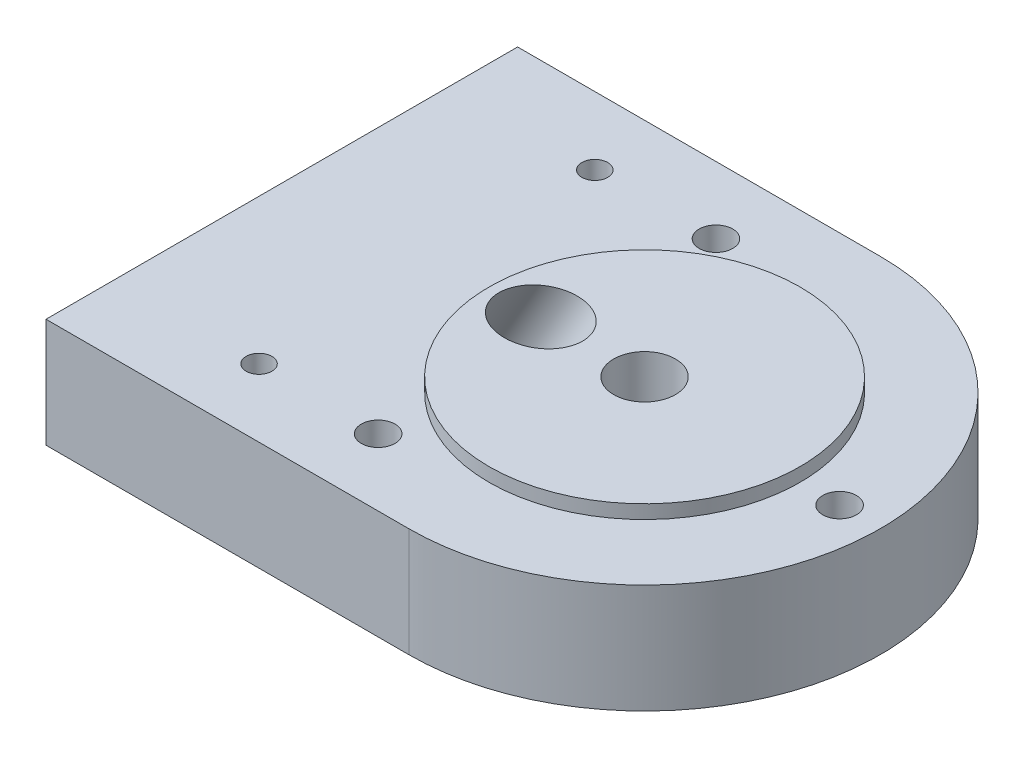
SolidWorks part; units mm, degrees
material "6061-T6 (SS)"
ref_plane "Front Plane" through (0, 0, 0) normal (0, 0, 1) x (1, 0, 0)
ref_plane "Top Plane" through (0, 0, 0) normal (0, 1, 0) x (1, 0, 0)
ref_plane "Right Plane" through (0, 0, 0) normal (1, 0, 0) x (0, 0, -1)
sketch "Sketch1" plane through (0, 0, 0) normal (0, 1, 0) x (1, 0, 0)
  line L1 (0, 0) -> (31.75, 0)
  line L2 (0, 0) -> (0, 41.275)
  line L3 (0, 41.275) -> (31.75, 41.275)
  line L4 (31.75, 0) -> (31.75, 41.275) construction
  arc A0 (31.75, 41.275) -> (31.75, 0) centre (31.75, 20.6375) cw
  dimension "D1" = 41.275
  dimension "D2" = 31.75
extrude "Boss-Extrude1" add sketch "Sketch1" along normal blind 9.5504
sketch "Sketch2" plane through (0, 9.5504, 0) normal (0, 1, 0) x (1, 0, 0)
  line L0 (31.75, 41.275) -> (31.75, 0) construction
  circle A0 centre (31.75, 20.6375) radius 13.6144
  arc A1 (31.75, 0) -> (31.75, 41.275) centre (31.75, 20.6375) ccw construction
  dimension "D1" = 27.2288
extrude "Boss-Extrude2" add sketch "Sketch2" along normal blind 1.1938
sketch "Sketch3" plane through (0, 10.7442, 0) normal (0, 1, 0) x (1, 0, 0)
  line L0 (18.1356, 20.6375) -> (45.3644, 20.6375) construction
  line L1 (31.75, 34.2519) -> (31.75, 7.0231) construction
  circle A0 centre (31.75, 20.6375) radius 13.6144 construction
  circle A1 centre (31.75, 20.6375) radius 13.6144 construction
  circle A3 centre (23.2156, 35.4203) radius 1.4732
  circle A4 centre (48.8188, 20.6375) radius 1.4732
  circle A5 centre (23.2156, 5.8547) radius 1.4732
  dimension "D4" = 2.9464
  dimension "D5" = 2.9464
  dimension "D6" = 2.9464
  dimension "D1" = 8.5344
  dimension "D2" = 14.7828
  dimension "D3" = 14.7828
  dimension "D7" = 17.0688
extrude "Cut-Extrude1" cut sketch "Sketch3" against normal through all
sketch "Sketch6" plane through (0, 0, 0) normal (0, -1, 0) x (-1, 0, 0)
  line L0 (-12.7, 0) -> (-12.7, 41.275) construction
  line L1 (0, 0) -> (-31.75, 0) construction
  line L2 (-31.75, 41.275) -> (0, 41.275) construction
  line L3 (0, 20.6375) -> (-52.3875, 20.6375) construction
  line L4 (0, 41.275) -> (0, 0) construction
  line L5 (-31.75, 0) -> (-31.75, 41.275) construction
  line L6 (-12.7, 5.9436) -> (0, 5.9436) construction
  line L7 (-12.7, 35.3314) -> (0, 35.3314) construction
  arc A0 (-31.75, 41.275) -> (-31.75, 0) centre (-31.75, 20.6375) ccw construction
  dimension "D1" = 12.7
  dimension "D2" = 29.3878
hole_wizard "#4-40 Tapped Hole1" positions "Sketch7" profile "Sketch8" tap size "#4-40" standard "ANSI Inch" end condition through all
sketch "Sketch7" plane through (0, 0, 0) normal (0, -1, 0) x (-1, 0, 0)
  point P0 (-12.7, 5.9436)
  point P3 (-12.7, 35.3314)
cosmetic thread "Hole Thread2" parameters "D2"=2.8448
cosmetic thread "Hole Thread3" parameters "D2"=2.8448
sketch "Sketch8" plane through (12.7, 0, -5.9436) normal (1, 0, 0) x (0, 0, -1)
  line L0 (0, 0) -> (0, 10.7442)
  line L1 (0, 10.7442) -> (1.1303, 10.7442)
  line L2 (1.1303, 10.7442) -> (1.1303, 0)
  line L5 (1.1303, 0) -> (0, 0)
  line L11 (0, -6.35) -> (0, 107.95) construction
  dimension "Thru Tap Drill Dia." = 2.2606
  dimension "Thru Tap Drill Depth" = 10.7442
hole_wizard "1/4-28 Tapped Hole1" positions "Sketch9" profile "Sketch10" tap size "1/4-28" standard "ANSI Inch" end condition through all
sketch "Sketch9" plane through (0, 0, 0) normal (0, -1, 0) x (-1, 0, 0)
  line L0 (-31.75, 0) -> (-31.75, 41.275) construction
  point P0 (-31.75, 20.6375)
sketch "Sketch10" plane through (31.75, 0, -20.6375) normal (1, 0, 0) x (0, 0, -1)
  line L0 (0, 0) -> (0, 10.7442)
  line L1 (0, 10.7442) -> (2.7051, 10.7442)
  line L2 (2.7051, 10.7442) -> (2.7051, 1.1249)
  line L3 (2.7051, 1.1249) -> (3.683, 0)
  line L5 (3.683, 0) -> (0, 0)
  line L6 (-2.7051, 1.1249) -> (-3.683, 0) construction
  line L11 (0, -6.35) -> (0, 107.95) construction
  dimension "Thru Tap Drill Dia." = 5.4102
  dimension "Thru Tap Drill Depth" = 10.7442
  dimension "Near C'Sink Dia." = 7.366
  dimension "Near C'Sink Angle" = 82
cosmetic thread "Hole Thread5" parameters "D2"=6.35
ref_plane "Plane2" through (0, 0, 0) normal (0.5, 0.866, 0) x (0, 0, 1)
sketch "Sketch11" plane through (0, 0, 0) normal (0.5, 0.866, 0) x (0, 0, 1)
  line L0 (-20.6375, 0) -> (-20.6375, 45.3689) construction
  line L1 (-41.275, 0) -> (0, 0) construction
  circle A0 centre (-20.6375, 14.2581) radius 3.175
  dimension "D1" = 6.35
  dimension "D2" = 14.2581
extrude "Cut-Extrude3" cut sketch "Sketch11" along normal through all
sketch "Sketch12" plane through (0, 0, 0) normal (0, -1, 0) x (1, 0, 0)
  circle A0 centre (31.75, -20.6375) radius 3.175
  dimension "D1" = 6.35
extrude "Cut-Extrude4" cut sketch "Sketch12" against normal blind 3.175
sketch "Sketch13" plane through (0, 0, 0) normal (-1, 0, 0) x (0, 0, 1)
  line L0 (-41.275, 4.7752) -> (0, 4.7752) construction
  line L1 (-41.275, 9.5504) -> (-41.275, 0) construction
  line L2 (0, 9.5504) -> (0, 0) construction
  line L3 (-28.575, 9.5504) -> (-28.575, 0) construction
  line L4 (-41.275, 9.5504) -> (0, 9.5504) construction
  line L5 (-41.275, 0) -> (0, 0) construction
  line L6 (-20.6375, 9.5504) -> (-20.6375, 0) construction
  dimension "D1" = 12.7
hole_wizard "#6-32 Tapped Hole1" positions "Sketch14" profile "Sketch15" tap size "#6-32" standard "ANSI Inch"
sketch "Sketch14" plane through (0, 0, 0) normal (-1, 0, 0) x (0, 0, 1)
  line L0 (-28.575, 9.5504) -> (-28.575, 0) construction
  point P0 (-28.575, 4.7752)
sketch "Sketch15" plane through (0, 4.7752, -28.575) normal (0, 1, 0) x (0, 0, 1)
  line L0 (0, 0) -> (0, 10.3377)
  line L1 (0, 10.3377) -> (1.3525, 9.525)
  line L2 (1.3525, 9.525) -> (1.3525, 0)
  line L5 (1.3525, 0) -> (0, 0)
  line L10 (0, 10.3377) -> (-1.3525, 9.525) construction
  line L11 (0, -6.35) -> (0, 107.95) construction
  dimension "Tap Drill Dia." = 2.7051
  dimension "Tap Drill Depth" = 9.525
  dimension "Drill Angle" = 118
cosmetic thread "Hole Thread6" parameters "D1"=7.0104, "D2"=3.5052
pattern_linear "LPattern1" count 2 spacing 15.875 along (0, 0, 1) of "#6-32 Tapped Hole1"
sketch "Sketch16" plane through (0, 9.5504, 0) normal (0, 1, 0) x (1, 0, 0)
  line L0 (31.75, 41.275) -> (31.75, 53.975)
  line L1 (31.75, 0) -> (31.75, -12.7)
  dimension "D1" = 12.7
  dimension "D2" = 12.7
ref_point "Point1"
ref_point "Point2"
ref_point "Point3"
